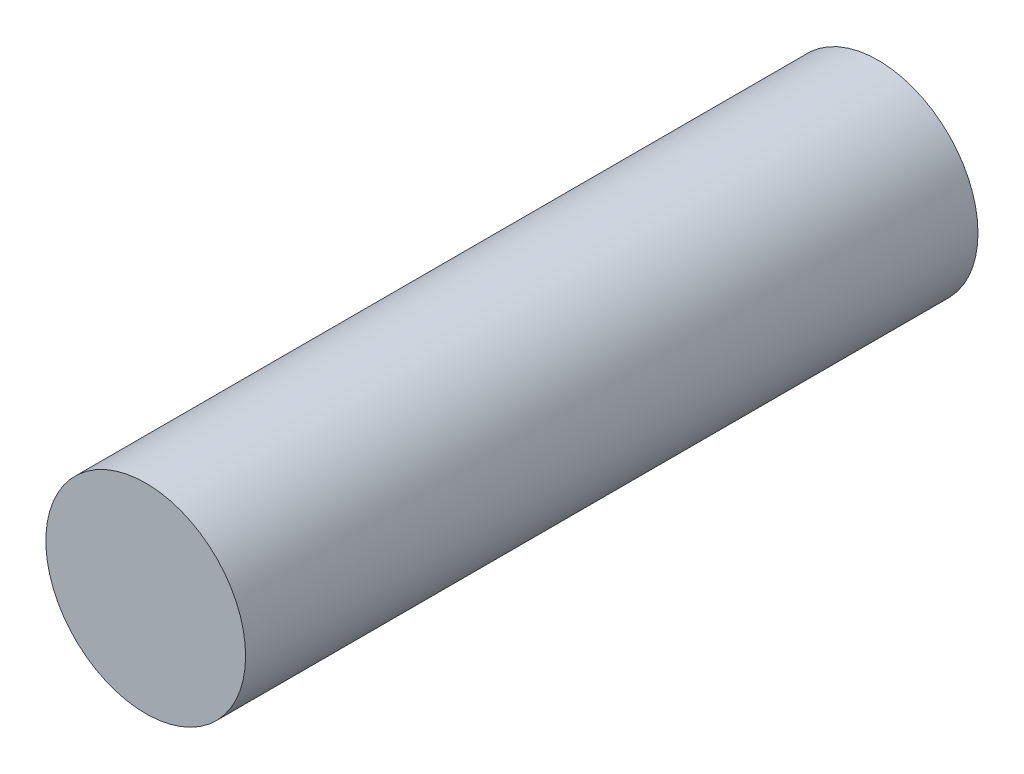
SolidWorks part; units mm, degrees
ref_plane "前视基准面" through (0, 0, 0) normal (0, 0, 1) x (1, 0, 0)
ref_plane "上视基准面" through (0, 0, 0) normal (0, 1, 0) x (1, 0, 0)
ref_plane "右视基准面" through (0, 0, 0) normal (1, 0, 0) x (0, 0, -1)
other "Configuration Table"
sketch "草图1" plane through (0, 0, 0) normal (0, 0, 1) x (1, 0, 0)
  circle A0 centre (0, 0) radius 6
extrude "凸台-拉伸1" add sketch "草图1" along normal mid plane 44
